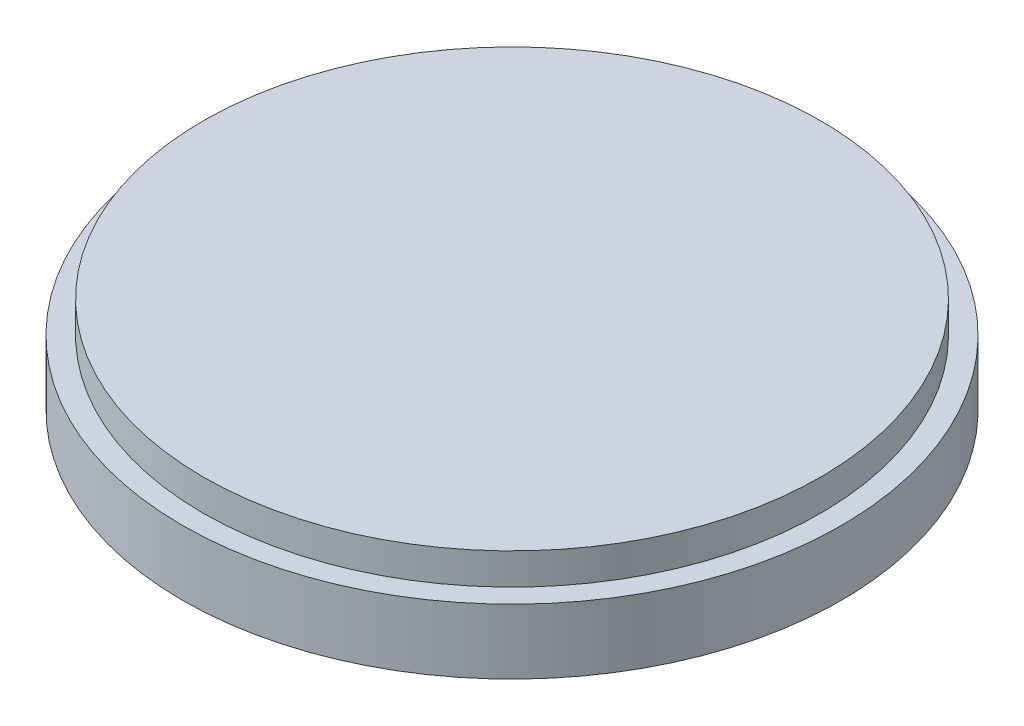
SolidWorks part; units mm, degrees
ref_plane "Front Plane" through (0, 0, 0) normal (0, 0, 1) x (1, 0, 0)
ref_plane "Top Plane" through (0, 0, 0) normal (0, 1, 0) x (1, 0, 0)
ref_plane "Right Plane" through (0, 0, 0) normal (1, 0, 0) x (0, 0, -1)
sketch "Sketch1" plane through (0, 0, 0) normal (0, 0, 1) x (1, 0, 0)
  line L0 (0, -13.2) -> (0, -7.6) construction
  line L1 (0, -13.2) -> (-26.5, -13.2) construction
  line L2 (-26.5, -13.2) -> (-26.5, -7.6) construction
  line L3 (-26.5, -7.6) -> (-31.5, -6.2)
  line L4 (-31.5, -6.2) -> (-31.5, 0)
  line L5 (-31.5, 0) -> (0, 0)
  line L6 (-26.5, -7.6) -> (0, -7.6)
  line L7 (0, -7.6) -> (0, 0)
  point P4 (0, 0)
  dimension "D1" = 26.5
  dimension "D2" = 5.6
  dimension "D3" = 1.4
  dimension "D4" = 6.2
  dimension "D5" = 31.5
revolve "Revolve1" add sketch "Sketch1" angle 360 about L0
sketch "Sketch2" plane through (0, -7.6, 0) normal (0, -1, 0) x (1, 0, 0)
  line L0 (-15.5563, -15.5563) -> (15.5563, 15.5563) construction
  line L1 (15.5563, -15.5563) -> (-15.5563, 15.5563) construction
  line L2 (0, 0) -> (0, 22) construction
  circle A0 centre (0, 0) radius 22 construction
  point P5 (0, 0)
  point P8 (0, 0)
  dimension "D1" = 44
  dimension "D2" = 45
hole_wizard "M3 Clearance Hole1" positions "Sketch3" profile "Sketch4" hole size "M3" standard "ANSI Metric"
sketch "Sketch3" plane through (0, -7.6, 0) normal (0, -1, 0) x (-1, 0, 0)
  point P0 (15.5563, -15.5563)
  point P3 (15.5563, 15.5563)
  point P6 (-15.5563, 15.5563)
  point P9 (-15.5563, -15.5563)
sketch "Sketch4" plane through (-15.5563, -7.6, 15.5563) normal (1, 0, 0) x (0, 0, -1)
  line L0 (0, 0) -> (0, 5.0215)
  line L1 (0, 5.0215) -> (1.7, 4)
  line L2 (1.7, 4) -> (1.7, 0)
  line L5 (1.7, 0) -> (0, 0)
  line L10 (0, 5.0215) -> (-1.7, 4) construction
  line L11 (0, -6.35) -> (0, 107.95) construction
  dimension "Hole Dia." = 3.4
  dimension "Hole Depth" = 4
  dimension "Drill Angle" = 118
sketch "Sketch5" plane through (0, 0, 0) normal (0, 1, 0) x (1, 0, 0)
  circle A2 centre (0, 0) radius 29.5
  circle A3 centre (0, 0) radius 29.5
  dimension "D1" = 2
extrude "Boss-Extrude1" add sketch "Sketch5" along normal blind 3
